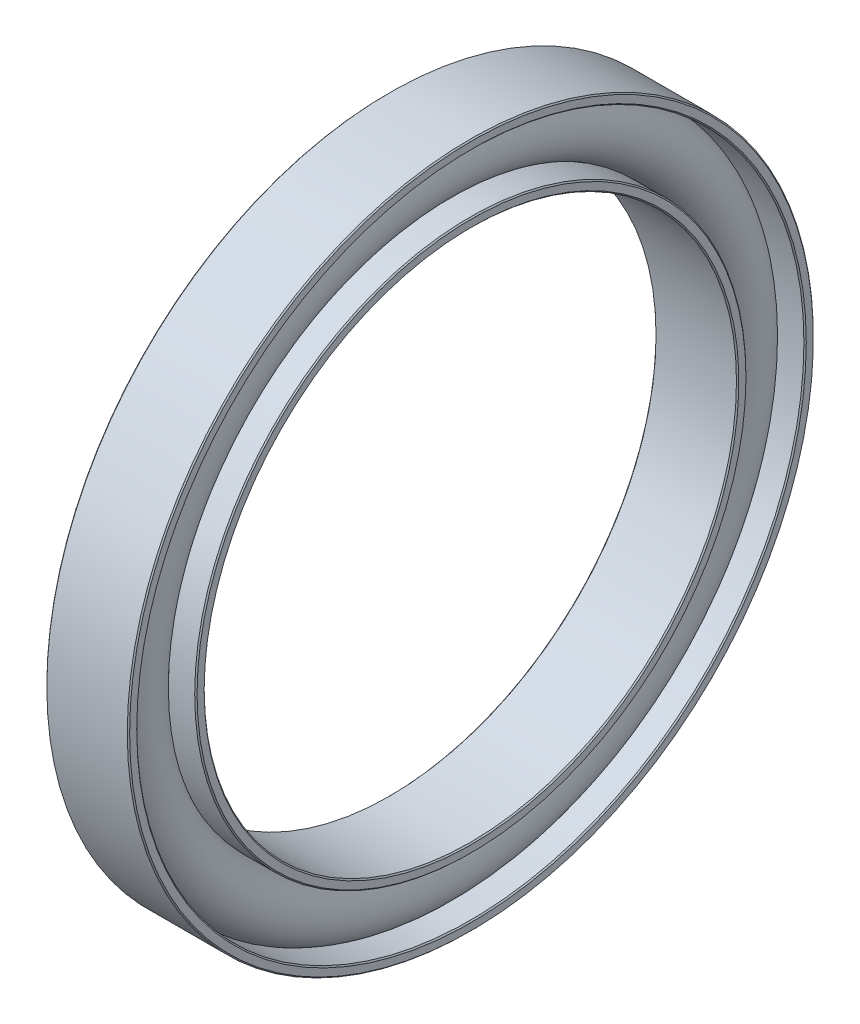
SolidWorks part; units mm, degrees
material "Alliage 1060"
ref_plane "Plan de face" through (0, 0, 0) normal (0, 0, 1) x (1, 0, 0)
ref_plane "Plan de dessus" through (0, 0, 0) normal (0, 1, 0) x (1, 0, 0)
ref_plane "Plan de droite" through (0, 0, 0) normal (1, 0, 0) x (0, 0, -1)
sketch "Esquisse1" plane through (0, 0, 0) normal (0, 0, 1) x (1, 0, 0)
  line L0 (-2.6614, 0) -> (2.6614, 0) construction
  line L1 (-3.5, 28.9) -> (-3.4, 29)
  line L2 (-3.4, 22.5) -> (3.4, 22.5)
  line L3 (-3.5, 22.6) -> (-3.5, 23.2)
  line L4 (-3.4, 29) -> (3.4, 29)
  line L5 (3.5, 22.6) -> (3.5, 23.2)
  line L6 (-3.4, 28.2) -> (-0.75, 28.2)
  line L7 (-3.5, 28.3) -> (-3.4, 28.2)
  line L8 (3.5, 28.3) -> (3.5, 28.9)
  line L9 (3.4, 29) -> (3.5, 28.9)
  line L10 (3.4, 23.3) -> (0.75, 23.3)
  line L11 (3.4, 28.2) -> (3.5, 28.3)
  line L12 (-4.5469, 25.75) -> (6.9877, 25.75) construction
  line L13 (-3.5, 28.3) -> (-3.5, 28.9)
  line L14 (0, 0) -> (0, 8.2024) construction
  line L15 (0.75, 28.2) -> (3.4, 28.2)
  line L16 (-0.75, 23.3) -> (-3.4, 23.3)
  line L17 (3.5, 23.2) -> (3.4, 23.3)
  line L18 (3.4, 22.5) -> (3.5, 22.6)
  line L19 (-3.5, 22.6) -> (-3.4, 22.5)
  line L20 (-3.4, 23.3) -> (-3.5, 23.2)
  arc A0 (-0.75, 28.2) -> (-0.75, 23.3) centre (0, 25.75) ccw
  arc A1 (0.75, 23.3) -> (0.75, 28.2) centre (0, 25.75) ccw
  point P13 (-3.5, 29)
  point P19 (-3.5, 28.2)
  point P21 (3.5, 29)
  point P23 (3.5, 28.2)
  point P27 (3.5, 23.3)
  point P30 (3.5, 22.5)
  point P34 (-3.5, 22.5)
  point P36 (-3.5, 23.3)
  dimension "D1" = 45
  dimension "D2" = 58
  dimension "D6" = 0.8
  dimension "D4" = 1.5
  dimension "D3" = 7
  dimension "D7" = 0.1
  dimension "D8" = 0.1
  dimension "D9" = 0.1
  dimension "D10" = 0.1
  dimension "D11" = 0.1
  dimension "D12" = 0.1
  dimension "D13" = 0.1
  dimension "D14" = 0.1
revolve "Révolution1" add sketch "Esquisse1" angle 360 about L0
